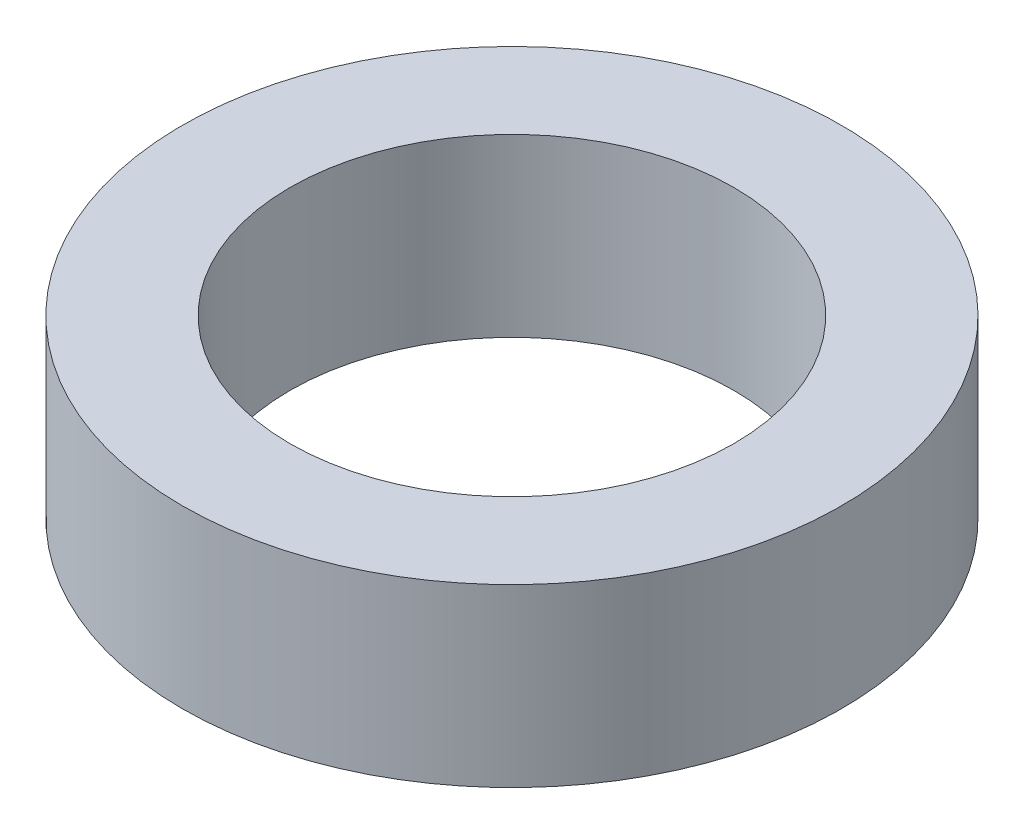
SolidWorks part; units mm, degrees
ref_plane "Front Plane" through (0, 0, 0) normal (0, 0, 1) x (1, 0, 0)
ref_plane "Top Plane" through (0, 0, 0) normal (0, 1, 0) x (1, 0, 0)
ref_plane "Right Plane" through (0, 0, 0) normal (1, 0, 0) x (0, 0, -1)
sketch "Sketch1" plane through (0, 0, 0) normal (0, 1, 0) x (1, 0, 0)
  circle A0 centre (0, 0) radius 15
  circle A1 centre (0, 0) radius 10.1
extrude "Revolved_Equivalent_Extrude" add sketch "Sketch1" along normal blind 8
equation "\"ValveDiameter\" = 50mm"
equation "\"MotorGearTeeth\" = 40"
equation "\"OutputGearTeeth\" = 80"
equation "\"GearModule\" = 1.5mm"
equation "\"PressureAngle\" = 20deg"
equation "\"GearCenterDistance\" = 90mm"
equation "\"GearWidth\" = 18mm"
equation "\"OutputShaftDiameter\" = 20mm"
equation "\"BearingOD\" = 47mm"
equation "\"BearingWidth\" = 14mm"
equation "\"PlateThickness\" = 6mm"
equation "\"ValveRotation\" = 90deg"
